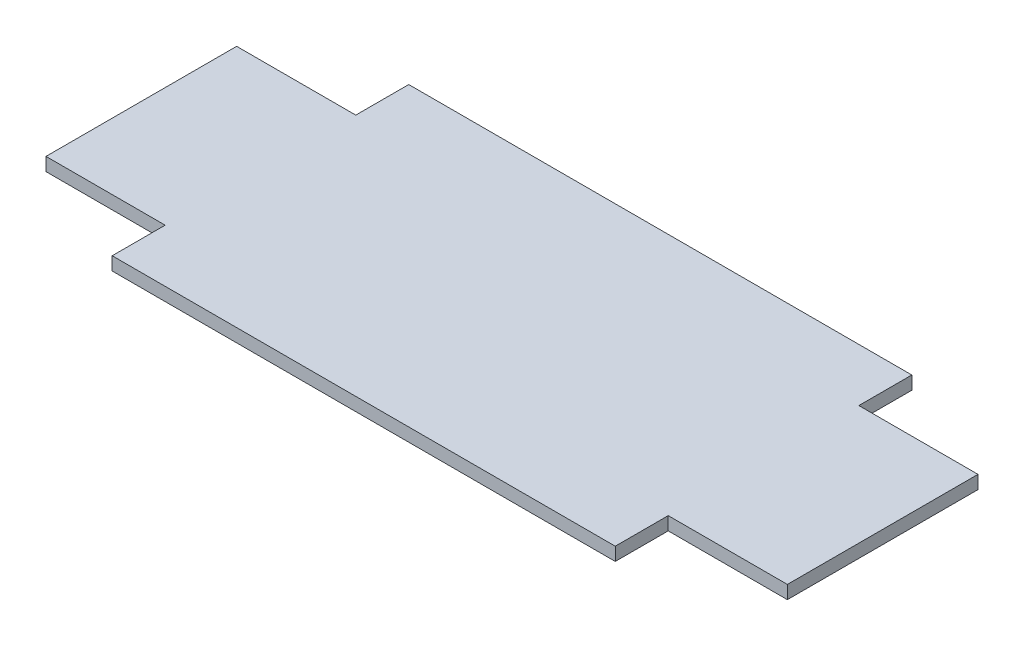
SolidWorks part; units mm, degrees
ref_plane "Front Plane" through (0, 0, 0) normal (0, 0, 1) x (1, 0, 0)
ref_plane "Top Plane" through (0, 0, 0) normal (0, 1, 0) x (1, 0, 0)
ref_plane "Right Plane" through (0, 0, 0) normal (1, 0, 0) x (0, 0, -1)
sketch "Sketch1" plane through (0, 0, 0) normal (0, 1, 0) x (1, 0, 0)
  line L0 (45, 0) -> (235, 0)
  line L1 (0, -20) -> (0, -92)
  line L2 (45, -112) -> (235, -112)
  line L3 (280, -92) -> (280, -20)
  line L4 (280, -56) -> (0, -56) construction
  line L5 (45, 0) -> (45, -112) construction
  line L6 (140, 0) -> (140, -112) construction
  line L7 (235, 0) -> (235, -112) construction
  line L8 (280, -20) -> (0, -20) construction
  line L9 (45, 0) -> (45, -20)
  line L10 (45, -20) -> (0, -20)
  line L11 (235, 0) -> (235, -20)
  line L12 (235, -20) -> (280, -20)
  line L13 (235, -92) -> (280, -92)
  line L14 (235, -112) -> (235, -92)
  line L15 (45, -92) -> (0, -92)
  line L16 (45, -112) -> (45, -92)
  dimension "D2" = 45
  dimension "D3" = 20
extrude "Boss-Extrude1" add sketch "Sketch1" along normal blind 5
